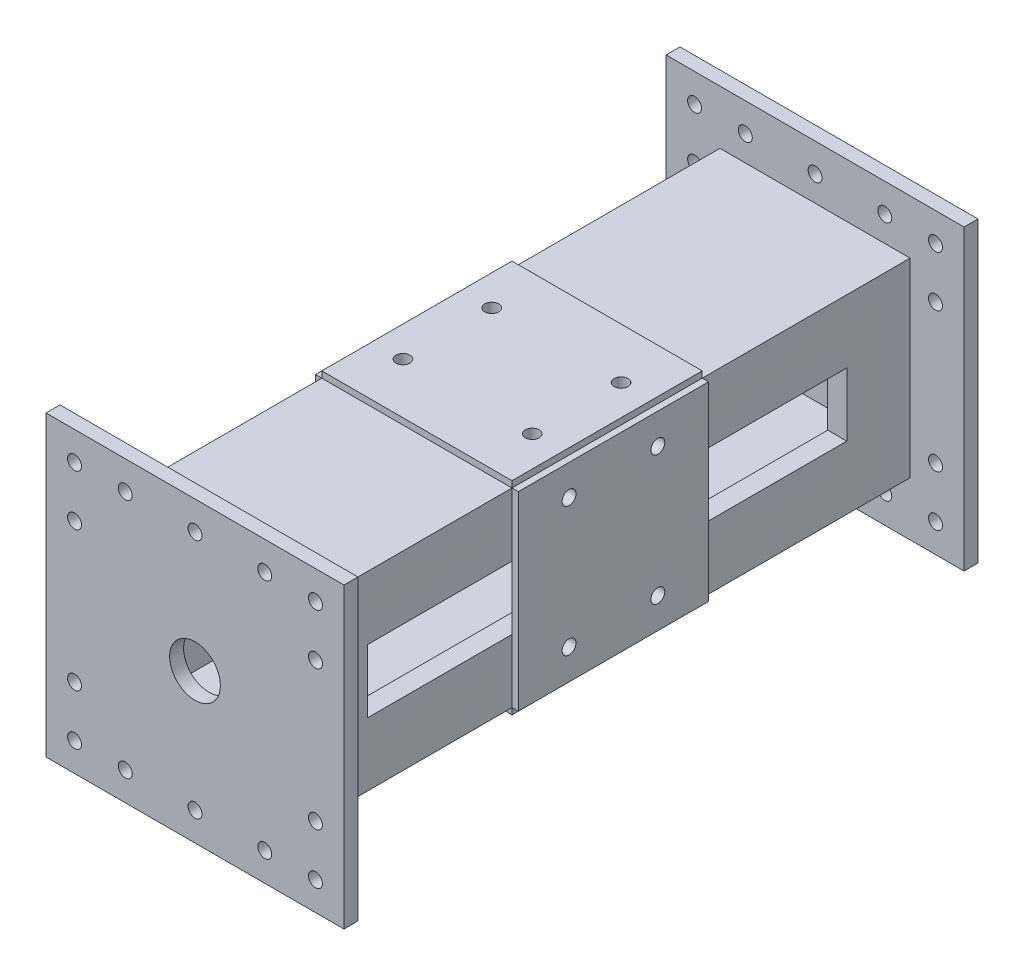
SolidWorks part; units mm, degrees
ref_plane "前视基准面" through (0, 0, 0) normal (0, 0, 1) x (1, 0, 0)
ref_plane "上视基准面" through (0, 0, 0) normal (0, 1, 0) x (1, 0, 0)
ref_plane "右视基准面" through (0, 0, 0) normal (1, 0, 0) x (0, 0, -1)
sketch "草图1" plane through (0, 0, 0) normal (0, 0, 1) x (1, 0, 0)
  line L1 (0, 0) -> (300, 0)
  line L2 (0, 0) -> (0, 300)
  line L3 (0, 300) -> (300, 300)
  line L4 (300, 0) -> (300, 300)
  dimension "D1" = 300
  dimension "D2" = 300
extrude "拉伸1" add sketch "草图1" along normal blind 956
sketch "草图2" plane through (0, 0, 956) normal (0, 0, 1) x (1, 0, 0)
  line L0 (300, 300) -> (0, 300) construction
  line L1 (30, 270) -> (270, 270)
  line L2 (30, 270) -> (30, 30)
  line L3 (30, 30) -> (270, 30)
  line L4 (270, 270) -> (270, 30)
  line L5 (0, 0) -> (300, 0) construction
  line L6 (0, 300) -> (0, 0) construction
  line L7 (300, 0) -> (300, 300) construction
  dimension "D1" = 30
  dimension "D2" = 30
  dimension "D3" = 30
  dimension "D4" = 30
extrude "切除-拉伸1" cut sketch "草图2" against normal through all
sketch "草图4" plane through (0, 0, 0) normal (-1, 0, 0) x (0, 0, 1)
  line L0 (0, 300) -> (0, 0) construction
  line L1 (100, 200) -> (856, 200)
  line L2 (100, 200) -> (100, 100)
  line L3 (100, 100) -> (856, 100)
  line L4 (856, 200) -> (856, 100)
  line L5 (956, 300) -> (956, 0) construction
  line L6 (956, 0) -> (0, 0) construction
  line L7 (956, 300) -> (0, 300) construction
  dimension "D1" = 100
  dimension "D2" = 100
  dimension "D3" = 100
  dimension "D4" = 100
extrude "切除-拉伸2" cut sketch "草图4" against normal through all
sketch "草图5" plane through (0, 0, 956) normal (0, 0, 1) x (1, 0, 0)
  line L0 (0, 300) -> (0, 0) construction
  line L1 (-85, 385) -> (385, 385)
  line L2 (-85, 385) -> (-85, -85)
  line L3 (-85, -85) -> (385, -85)
  line L4 (385, 385) -> (385, -85)
  line L5 (0, 0) -> (300, 0) construction
  dimension "D1" = 470
  dimension "D2" = 470
  dimension "D3" = 85
  dimension "D4" = 85
extrude "拉伸2" add sketch "草图5" along normal blind 22
sketch "草图6" plane through (0, 0, 0) normal (0, 0, -1) x (-1, 0, 0)
  line L0 (0, 0) -> (-300, 0) construction
  line L1 (-385, 385) -> (85, 385)
  line L2 (-385, 385) -> (-385, -85)
  line L3 (-385, -85) -> (85, -85)
  line L4 (85, 385) -> (85, -85)
  line L5 (-300, 300) -> (0, 300) construction
  line L6 (-300, 0) -> (-300, 300) construction
  line L7 (0, 300) -> (0, 0) construction
  dimension "D1" = 85
  dimension "D2" = 85
  dimension "D3" = 85
  dimension "D4" = 85
extrude "拉伸3" add sketch "草图6" along normal blind 22
sketch "草图7" plane through (0, 0, 978) normal (0, 0, 1) x (1, 0, 0)
  line L0 (-85, -85) -> (385, -85) construction
  line L1 (385, -85) -> (385, 385) construction
  circle A0 centre (-40, -40) radius 11
  circle A1 centre (40, -40) radius 11
  circle A2 centre (150, -40) radius 11
  circle A3 centre (260, -40) radius 11
  circle A4 centre (340, -40) radius 11
  circle A5 centre (-40, 340) radius 11
  circle A6 centre (40, 340) radius 11
  circle A7 centre (150, 340) radius 11
  circle A8 centre (260, 340) radius 11
  circle A9 centre (340, 340) radius 11
  circle A10 centre (-40, 40) radius 11
  circle A11 centre (-40, 260) radius 11
  circle A12 centre (340, 40) radius 11
  circle A13 centre (340, 260) radius 11
  dimension "D1" = 80
  dimension "D2" = 80
  dimension "D3" = 220
  dimension "D4" = 45
  dimension "D5" = 80
  dimension "D6" = 80
  dimension "D7" = 110
  dimension "D8" = 110
  dimension "D9" = 45
extrude "切除-拉伸3" cut sketch "草图7" against normal through all
sketch "草图9" plane through (0, 300, 0) normal (0, 1, 0) x (1, 0, 0)
  line L0 (0, -100) -> (0, -856) construction
  line L1 (0, -328) -> (300, -328)
  line L2 (0, -328) -> (0, -628)
  line L3 (0, -628) -> (300, -628)
  line L4 (300, -328) -> (300, -628)
  line L5 (300, -956) -> (300, 0) construction
  point P8 (300, -478)
  dimension "D1" = 300
  dimension "D2" = 150
extrude "拉伸4" add sketch "草图9" along normal blind 10
sketch "草图10" plane through (0, 0, 0) normal (0, -1, 0) x (1, 0, 0)
  line L0 (0, 956) -> (0, 0) construction
  line L1 (300, 328) -> (0, 328)
  line L2 (300, 328) -> (300, 628)
  line L3 (300, 628) -> (0, 628)
  line L4 (0, 328) -> (0, 628)
  line L5 (300, 956) -> (300, 0) construction
  line L6 (0, 956) -> (300, 956) construction
  point P8 (0, 478)
  dimension "D1" = 300
  dimension "D2" = 150
extrude "拉伸5" add sketch "草图10" along normal blind 10
sketch "草图11" plane through (300, 0, 0) normal (1, 0, 0) x (0, 0, -1)
  line L1 (-628, 0) -> (-328, 0)
  line L2 (-628, 0) -> (-628, 300)
  line L3 (-628, 300) -> (-328, 300)
  line L4 (-328, 0) -> (-328, 300)
extrude "拉伸6" add sketch "草图11" along normal blind 10
sketch "草图12" plane through (0, 0, 0) normal (-1, 0, 0) x (0, 0, 1)
  line L1 (628, 300) -> (328, 300)
  line L2 (628, 300) -> (628, 0)
  line L3 (628, 0) -> (328, 0)
  line L4 (328, 300) -> (328, 0)
extrude "拉伸7" add sketch "草图12" along normal blind 10
sketch "草图13" plane through (-10, 0, 0) normal (-1, 0, 0) x (0, 0, 1)
  line L1 (328, 200) -> (328, 100) construction
  line L3 (628, 300) -> (328, 300) construction
  circle A0 centre (408, 48) radius 11
  circle A1 centre (408, 252) radius 11
  circle A2 centre (548, 252) radius 11
  circle A3 centre (548, 48) radius 11
  point P11 (328, 150)
  point P14 (478, 300)
  dimension "D1" = 140
  dimension "D2" = 204
  dimension "D3" = 70
  dimension "D4" = 102
extrude "切除-拉伸4" cut sketch "草图13" against normal through all
sketch "草图14" plane through (0, 310, 0) normal (0, 1, 0) x (1, 0, 0)
  line L0 (300, -328) -> (0, -328) construction
  line L1 (300, -628) -> (300, -328) construction
  circle A0 centre (48, -548) radius 11
  circle A1 centre (252, -548) radius 11
  circle A2 centre (252, -408) radius 11
  circle A3 centre (48, -408) radius 11
  point P8 (150, -328)
  point P11 (300, -478)
  dimension "D1" = 204
  dimension "D2" = 140
  dimension "D3" = 102
  dimension "D4" = 70
extrude "切除-拉伸5" cut sketch "草图14" against normal through all
sketch "草图15" plane through (0, 0, 978) normal (0, 0, 1) x (1, 0, 0)
  line L0 (385, -85) -> (385, 385) construction
  line L1 (385, 385) -> (-85, 385) construction
  circle A0 centre (150, 150) radius 40
  dimension "D1" = 235
  dimension "D2" = 235
extrude "切除-拉伸6" cut sketch "草图15" against normal through all
